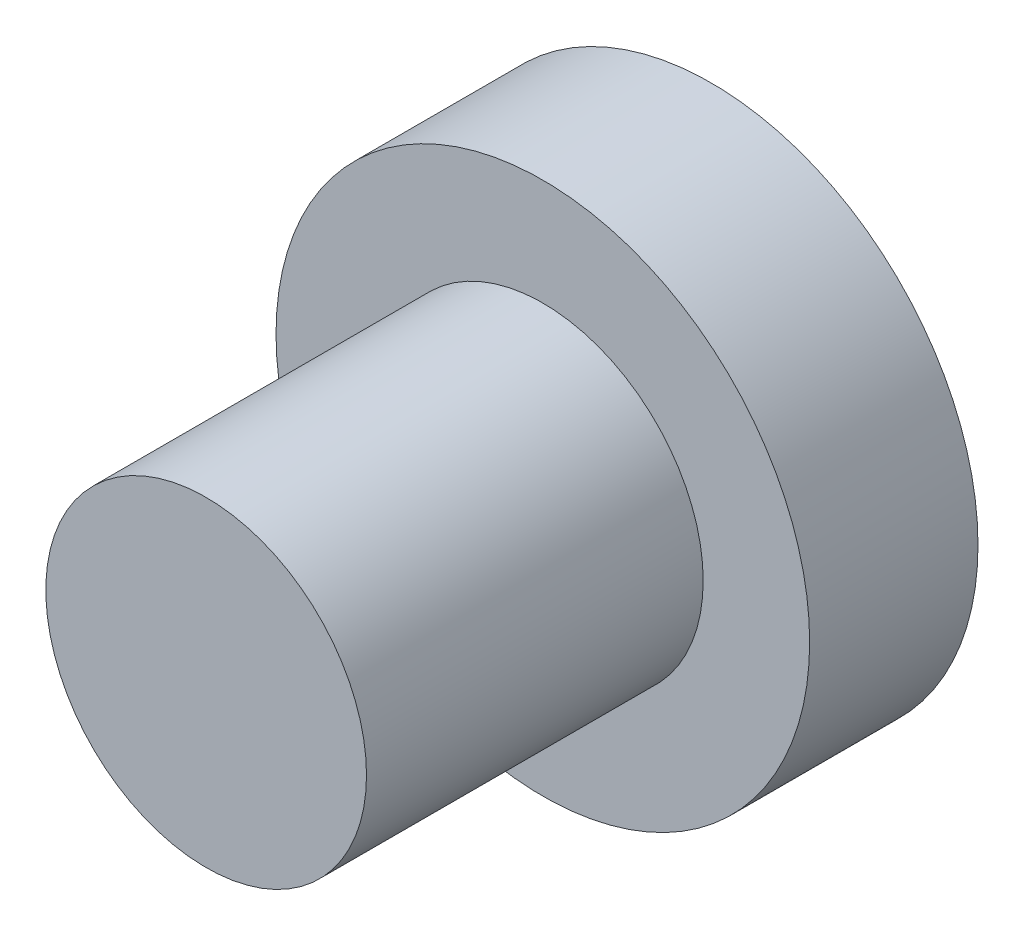
SolidWorks part; units mm, degrees
ref_plane "Front" through (0, 0, 0) normal (0, 0, 1) x (1, 0, 0)
ref_plane "Top" through (0, 0, 0) normal (0, 1, 0) x (1, 0, 0)
ref_plane "Right" through (0, 0, 0) normal (1, 0, 0) x (0, 0, -1)
sketch "Sketch1" plane through (0, 0, 0) normal (0, 0, 1) x (1, 0, 0)
  circle A0 centre (0, 0) radius 7.925
extrude "Extrude1" add sketch "Sketch1" along normal blind 5
sketch "Sketch2" plane through (0, 0, 5) normal (0, 0, 1) x (1, 0, 0)
  circle A0 centre (0, 0) radius 4.7625
extrude "Extrude2" add sketch "Sketch2" along normal blind 10
